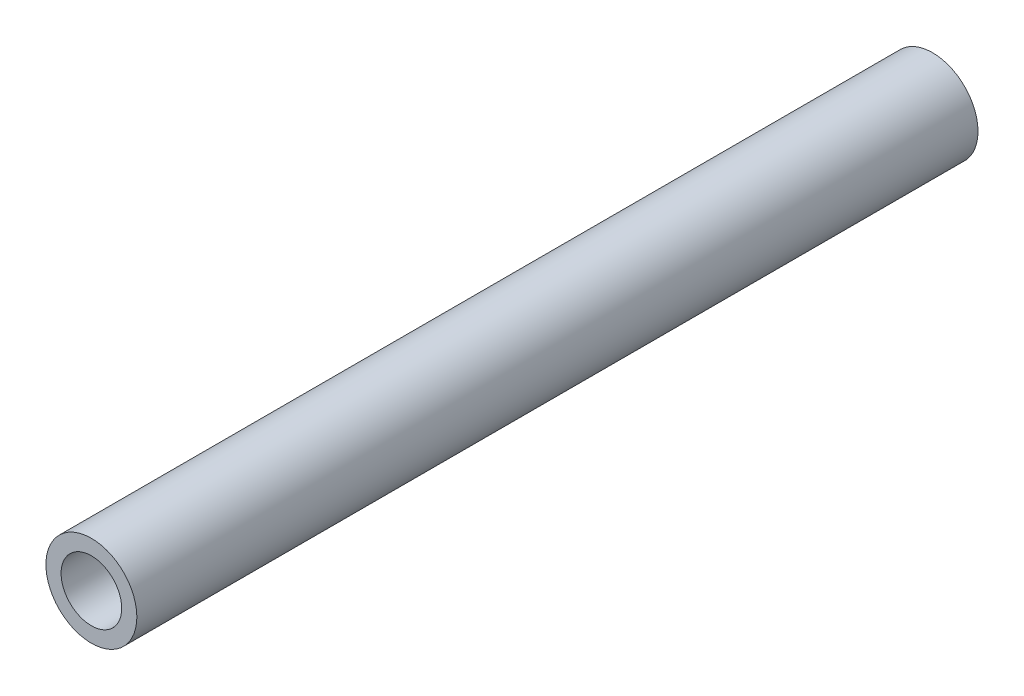
SolidWorks part; units mm, degrees
material "炭素鋼(普通)"
ref_plane "正面" through (0, 0, 0) normal (0, 0, 1) x (1, 0, 0)
ref_plane "平面" through (0, 0, 0) normal (0, 1, 0) x (1, 0, 0)
ref_plane "右側面" through (0, 0, 0) normal (1, 0, 0) x (0, 0, -1)
sketch "ｽｹｯﾁ1" plane through (0, 0, 0) normal (0, 0, 1) x (1, 0, 0)
  circle A0 centre (0, 0) radius 3
  dimension "D1" = 6
extrude "押し出し-薄板1" add sketch "ｽｹｯﾁ1" along normal blind 55.5 thin thin type one direction reverse wall 1
